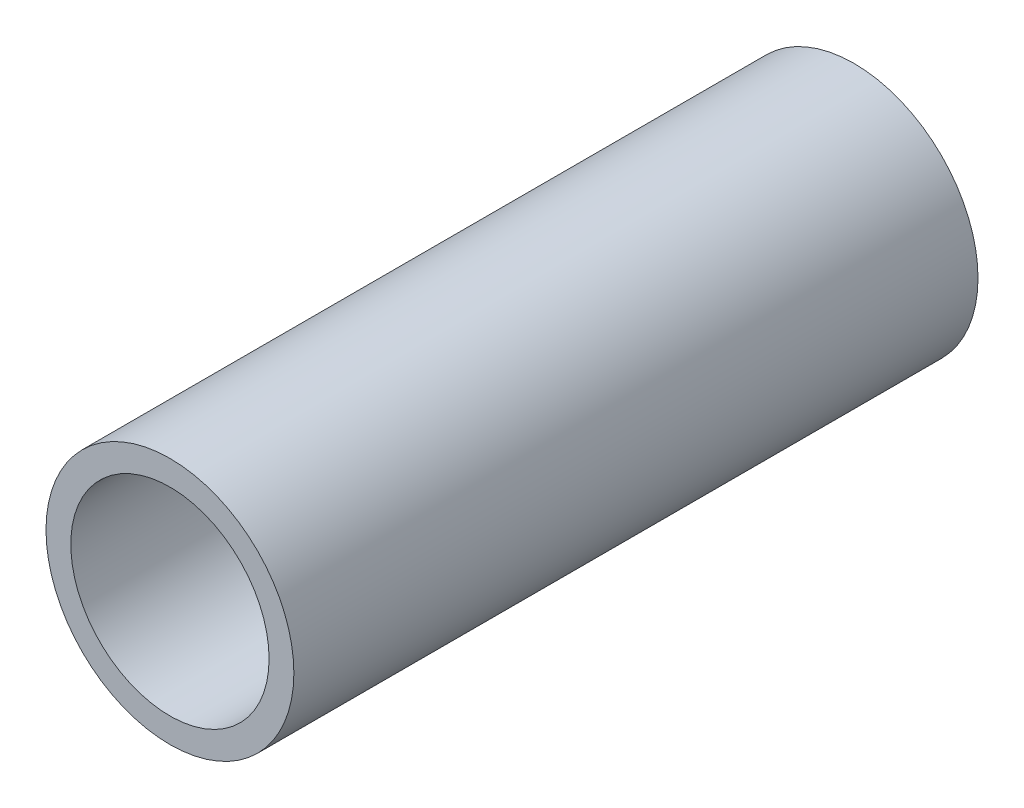
SolidWorks part; units mm, degrees
ref_plane "Спереди" through (0, 0, 0) normal (0, 0, 1) x (1, 0, 0)
ref_plane "Сверху" through (0, 0, 0) normal (0, 1, 0) x (1, 0, 0)
ref_plane "Справа" through (0, 0, 0) normal (1, 0, 0) x (0, 0, -1)
sketch "Sketch1" plane through (0, 0, 0) normal (0, 0, 1) x (1, 0, 0)
  circle A0 centre (0, 0) radius 1
  circle A1 centre (0, 0) radius 1.25
extrude "Extrude1" add sketch "Sketch1" against normal blind 6.9
